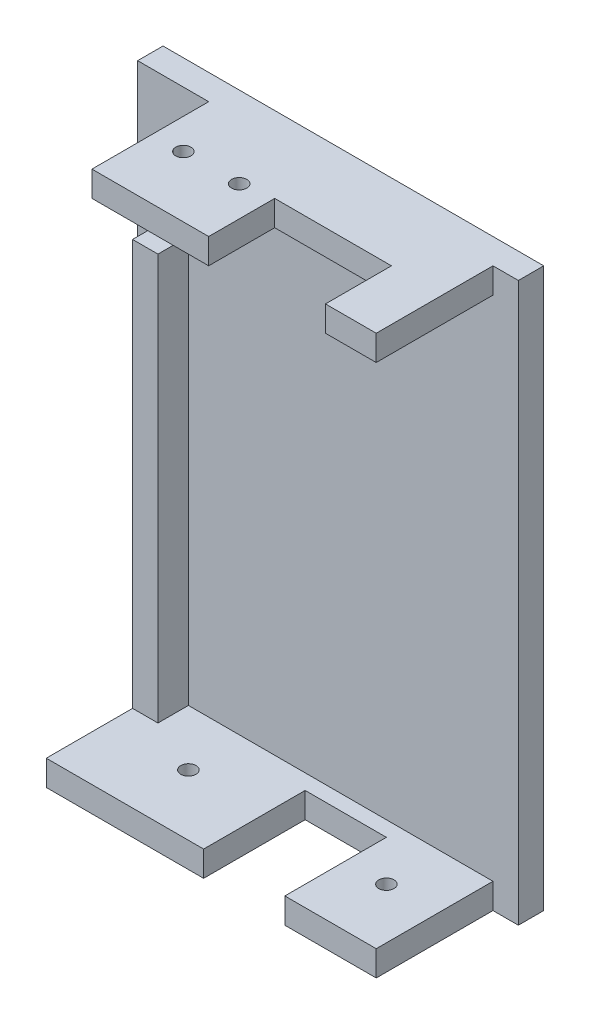
SolidWorks part; units mm, degrees
ref_plane "前基準面" through (0, 0, 0) normal (0, 0, 1) x (1, 0, 0)
ref_plane "上基準面" through (0, 0, 0) normal (0, 1, 0) x (1, 0, 0)
ref_plane "右基準面" through (0, 0, 0) normal (1, 0, 0) x (0, 0, -1)
sketch "草圖1" plane through (0, 0, 0) normal (0, 0, 1) x (1, 0, 0)
  line L1 (-28.1443, 35.3682) -> (46.8557, 35.3682)
  line L2 (-28.1443, 35.3682) -> (-28.1443, -74.6318)
  line L3 (-28.1443, -74.6318) -> (46.8557, -74.6318)
  line L4 (46.8557, 35.3682) -> (46.8557, -74.6318)
  dimension "D1" = 75
  dimension "D2" = 110
extrude "填料-伸長1" add sketch "草圖1" along normal blind 5
sketch "草圖2" plane through (0, 0, 5) normal (0, 0, 1) x (1, 0, 0)
  line L0 (-28.1443, -74.6318) -> (46.8557, -74.6318) construction
  line L1 (-23.1443, -74.6318) -> (41.8557, -74.6318)
  line L2 (-23.1443, -74.6318) -> (-23.1443, -69.6318)
  line L3 (-23.1443, -69.6318) -> (41.8557, -69.6318)
  line L4 (41.8557, -74.6318) -> (41.8557, -69.6318)
  line L5 (-28.1443, 35.3682) -> (-28.1443, -74.6318) construction
  line L6 (46.8557, -74.6318) -> (46.8557, 35.3682) construction
  line L8 (-14.1443, 30.3682) -> (41.8557, 30.3682)
  line L9 (-14.1443, 30.3682) -> (-14.1443, 35.3682)
  line L10 (-14.1443, 35.3682) -> (41.8557, 35.3682)
  line L11 (41.8557, 30.3682) -> (41.8557, 35.3682)
  dimension "D1" = 5
  dimension "D2" = 5
  dimension "D3" = 5
  dimension "D4" = 5
  dimension "D5" = 105
  dimension "D6" = 56
  dimension "D7" = 5
extrude "填料-伸長2" add sketch "草圖2" along normal blind 23
sketch "草圖3" plane through (0, 35.3682, 0) normal (0, 1, 0) x (1, 0, 0)
  line L1 (41.8557, -28) -> (-14.1443, -28) construction
  line L2 (41.8557, -28) -> (41.8557, -5) construction
  line L3 (31.8557, -28) -> (8.8557, -28)
  line L4 (31.8557, -28) -> (31.8557, -15)
  line L5 (31.8557, -15) -> (8.8557, -15)
  line L6 (8.8557, -28) -> (8.8557, -15)
  line L7 (46.8557, 0) -> (-28.1443, 0) construction
  line L8 (41.8557, -28) -> (-14.1443, -28) construction
  line L9 (-14.1443, -28) -> (-14.1443, -5) construction
  circle A0 centre (2.8557, -16) radius 1.5
  circle A1 centre (-8.1443, -16) radius 1.5
  dimension "D1" = 3
  dimension "D7" = 3
  dimension "D2" = 6
  dimension "D3" = 12
  dimension "D4" = 10
  dimension "D5" = 23
  dimension "D6" = 15
  dimension "D8" = 12
  dimension "D9" = 6
extrude "除料-伸長1" cut sketch "草圖3" against normal blind 10
sketch "草圖5" plane through (0, -69.6318, 0) normal (0, 1, 0) x (1, 0, 0)
  line L0 (41.8557, -28) -> (-23.1443, -28) construction
  line L1 (23.8557, -28) -> (7.8557, -28)
  line L2 (23.8557, -28) -> (23.8557, -8)
  line L3 (23.8557, -8) -> (7.8557, -8)
  line L4 (7.8557, -28) -> (7.8557, -8)
  line L5 (41.8557, -28) -> (41.8557, -5) construction
  line L6 (41.8557, -5) -> (-23.1443, -5) construction
  dimension "D1" = 18
  dimension "D2" = 34
  dimension "D3" = 3
extrude "除料-伸長2" cut sketch "草圖5" against normal up to next
sketch "草圖6" plane through (0, -69.6318, 0) normal (0, 1, 0) x (1, 0, 0)
  line L0 (41.8557, -28) -> (41.8557, -5) construction
  line L1 (41.8557, -28) -> (23.8557, -28) construction
  circle A0 centre (31.8557, -16) radius 1.5
  dimension "D1" = 3
  dimension "D2" = 10
  dimension "D3" = 12
extrude "除料-伸長3" cut sketch "草圖6" against normal up to next
sketch "草圖7" plane through (0, -74.6318, 0) normal (0, -1, 0) x (1, 0, 0)
  line L0 (-23.1443, 28) -> (-23.1443, 5) construction
  line L1 (-23.1443, 28) -> (7.8557, 28) construction
  circle A0 centre (-7.1443, 16) radius 1.5
  dimension "D1" = 3
  dimension "D2" = 16
  dimension "D3" = 12
extrude "除料-伸長4" cut sketch "草圖7" against normal up to next
sketch "草圖8" plane through (0, 0, 5) normal (0, 0, 1) x (1, 0, 0)
  line L1 (-23.1443, -69.6318) -> (-18.1443, -69.6318)
  line L2 (-23.1443, -69.6318) -> (-23.1443, 10.3682)
  line L3 (-23.1443, 10.3682) -> (-18.1443, 10.3682)
  line L4 (-18.1443, -69.6318) -> (-18.1443, 10.3682)
  dimension "D1" = 5
  dimension "D2" = 80
extrude "填料-伸長3" add sketch "草圖8" along normal blind 6
